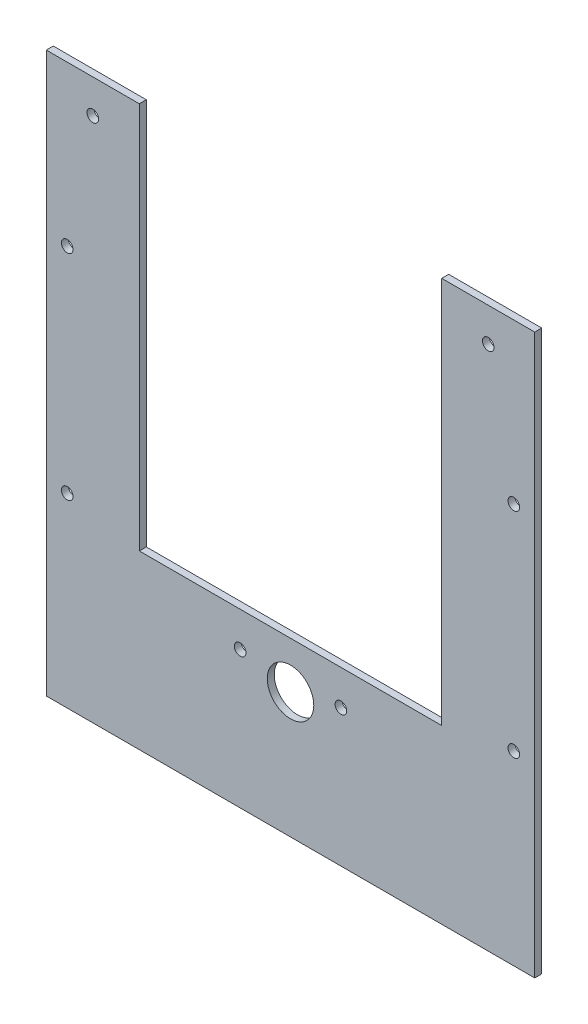
SolidWorks part; units mm, degrees
ref_plane "Alzado" through (0, 0, 0) normal (0, 0, 1) x (1, 0, 0)
ref_plane "Planta" through (0, 0, 0) normal (0, 1, 0) x (1, 0, 0)
ref_plane "Vista lateral" through (0, 0, 0) normal (1, 0, 0) x (0, 0, -1)
sketch "Croquis1" plane through (0, 0, 0) normal (0, 0, 1) x (1, 0, 0)
  line L0 (-79.4984, 944.1284) -> (-79.4984, 777.6284)
  line L1 (90.5016, 703.6284) -> (-119.4984, 703.6284)
  line L2 (90.5016, 703.6284) -> (90.5016, 944.1284)
  line L3 (90.5016, 944.1284) -> (50.5016, 944.1284)
  line L4 (-119.4984, 703.6284) -> (-119.4984, 944.1284)
  line L5 (-79.4984, 777.6284) -> (50.5016, 777.6284)
  line L6 (50.5016, 777.6284) -> (50.5016, 944.1284)
  line L7 (-79.4984, 944.1284) -> (-119.4984, 944.1284)
  circle A0 centre (70.5016, 929.6284) radius 2.5
  circle A1 centre (81.5016, 875.6184) radius 2.5
  circle A2 centre (81.5016, 783.6184) radius 2.5
  circle A3 centre (-36.1651, 762.6284) radius 2.5
  circle A4 centre (-110.4984, 783.6184) radius 2.5
  circle A5 centre (-110.4984, 875.6184) radius 2.5
  circle A6 centre (-99.4984, 929.6284) radius 2.5
  circle A7 centre (7.1683, 762.6284) radius 2.5
  circle A8 centre (-14.4984, 757.6284) radius 10
extrude "Saliente-Extruir1" add sketch "Croquis1" along normal blind 3
